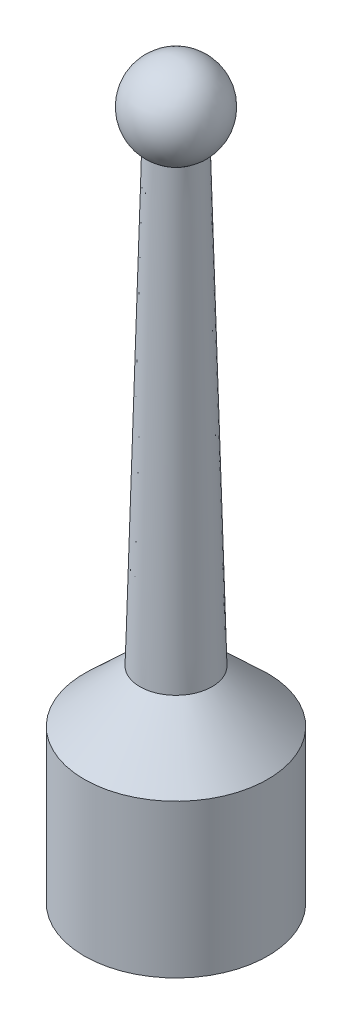
SolidWorks part; units mm, degrees
ref_plane "Front Plane" through (0, 0, 0) normal (0, 0, 1) x (1, 0, 0)
ref_plane "Top Plane" through (0, 0, 0) normal (0, 1, 0) x (1, 0, 0)
ref_plane "Right Plane" through (0, 0, 0) normal (1, 0, 0) x (0, 0, -1)
sketch "Sketch1" plane through (0, 0, 0) normal (0, 0, 1) x (1, 0, 0)
  line L0 (0, 0) -> (0, 84.1767) construction
  line L1 (0, 0) -> (7.4295, 0)
  line L2 (7.4295, 0) -> (7.4295, 12.3952)
  line L3 (7.4295, 12.3952) -> (2.921, 16.637)
  line L4 (2.921, 16.637) -> (1.9685, 52.9851)
  line L5 (0, 59.3344) -> (0, 0)
  arc A0 (1.9685, 52.9851) -> (0, 59.3344) centre (0, 55.8546) ccw
  dimension "D5" = 3.4798
  dimension "D1" = 14.859
  dimension "D2" = 16.637
  dimension "D3" = 12.3952
  dimension "D4" = 5.842
  dimension "D6" = 3.937
  dimension "D7" = 59.3344
revolve "Revolve1" add sketch "Sketch1" angle 360 about L0
